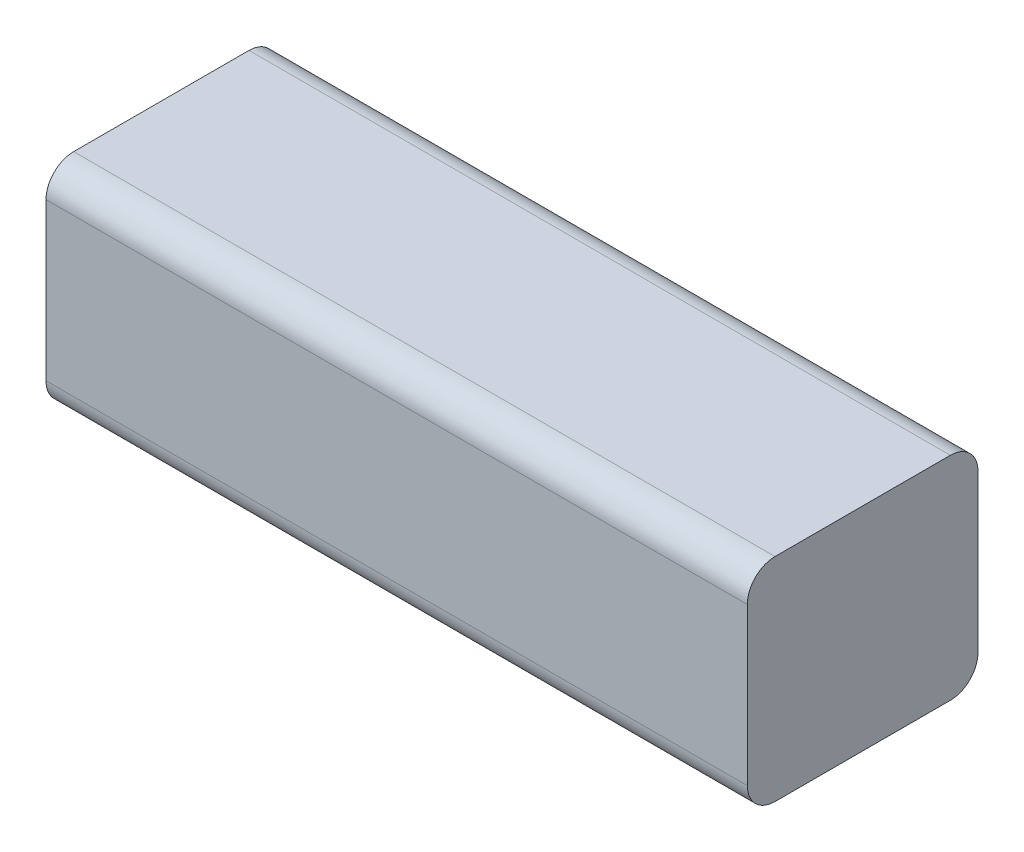
SolidWorks part; units mm, degrees
ref_plane "Front Plane" through (0, 0, 0) normal (0, 0, 1) x (1, 0, 0)
ref_plane "Top Plane" through (0, 0, 0) normal (0, 1, 0) x (1, 0, 0)
ref_plane "Right Plane" through (0, 0, 0) normal (1, 0, 0) x (0, 0, -1)
sketch "Sketch1" plane through (0, 0, 0) normal (0, 1, 0) x (1, 0, 0)
  line L1 (-38, 12.5) -> (38, 12.5)
  line L2 (-38, 12.5) -> (-38, -12.5)
  line L3 (-38, -12.5) -> (38, -12.5)
  line L4 (38, 12.5) -> (38, -12.5)
  line L5 (-38, 12.5) -> (38, -12.5) construction
  line L6 (-38, -12.5) -> (38, 12.5) construction
  point P0 (0, 0)
  dimension "D1" = 76
  dimension "D2" = 25
extrude "Boss-Extrude1" add sketch "Sketch1" along normal blind 23
fillet "Fillet1" radius 3 4 edges at (0, 0, -12.5) (0, 0, 12.5) (0, 23, -12.5) (0, 23, 12.5)
